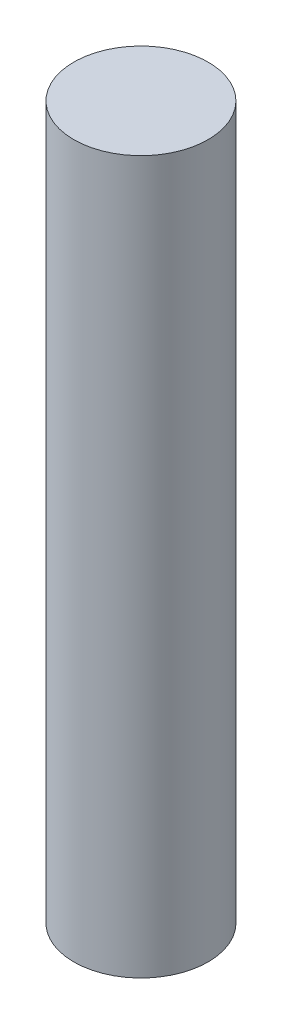
SolidWorks part; units mm, degrees
ref_plane "前视基准面" through (0, 0, 0) normal (0, 0, 1) x (1, 0, 0)
ref_plane "上视基准面" through (0, 0, 0) normal (0, 1, 0) x (1, 0, 0)
ref_plane "右视基准面" through (0, 0, 0) normal (1, 0, 0) x (0, 0, -1)
other "Configuration Table"
sketch "草图1" plane through (0, 0, 0) normal (0, 1, 0) x (1, 0, 0)
  circle A0 centre (0, 0) radius 1.415
  dimension "D1" = 2.83
extrude "凸台-拉伸2" add sketch "草图1" along normal blind 15
